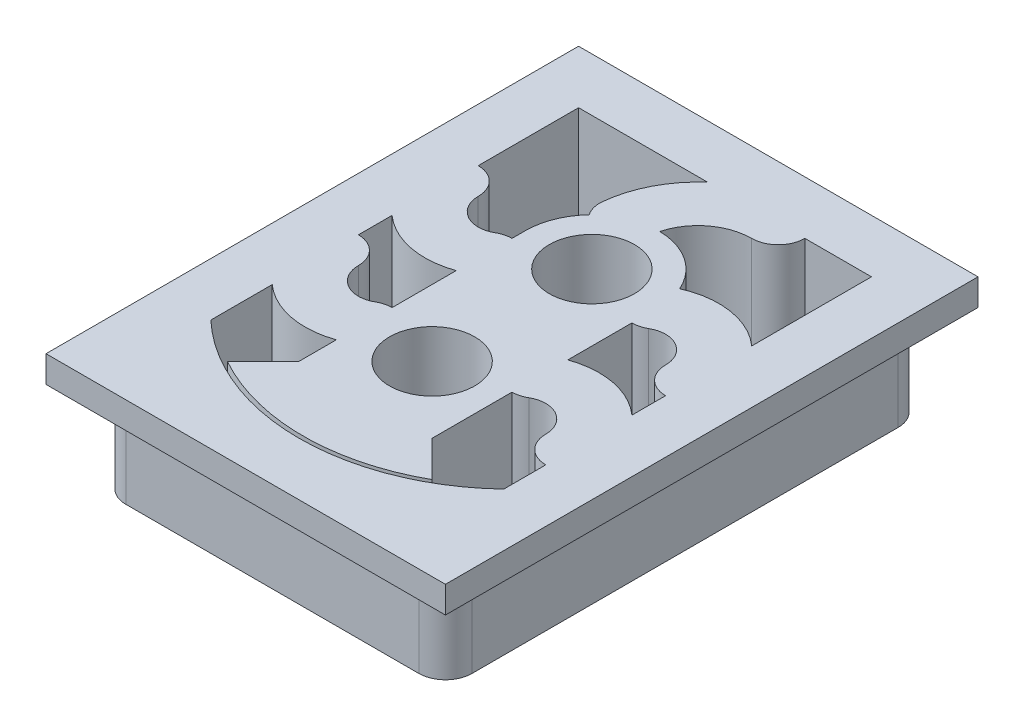
SolidWorks part; units mm, degrees
ref_plane "Front Plane" through (0, 0, 0) normal (0, 0, 1) x (1, 0, 0)
ref_plane "Top Plane" through (0, 0, 0) normal (0, 1, 0) x (1, 0, 0)
ref_plane "Right Plane" through (0, 0, 0) normal (1, 0, 0) x (0, 0, -1)
sketch "Sketch1" plane through (0, 0, 0) normal (0, 1, 0) x (1, 0, 0)
  line L1 (-6.5, -9) -> (6.5, -9)
  line L2 (-6.5, -9) -> (-6.5, 9)
  line L3 (-6.5, 9) -> (6.5, 9)
  line L4 (6.5, -9) -> (6.5, 9)
  line L5 (-6.5, -9) -> (6.5, 9) construction
  line L6 (-6.5, 9) -> (6.5, -9) construction
  point P0 (0, 0)
  dimension "D1" = 18
  dimension "D2" = 13
extrude "Boss-Extrude1" add sketch "Sketch1" along normal blind 3.4
sketch "Sketch2" plane through (0, 3.4, 0) normal (0, 1, 0) x (1, 0, 0)
  line L8 (7.5, -10) -> (7.5, 10)
  line L9 (7.5, 10) -> (-7.5, 10)
  line L10 (-7.5, 10) -> (-7.5, -10)
  line L11 (-7.5, -10) -> (7.5, -10)
  line L12 (7.5, -10) -> (7.5, 10)
  line L13 (7.5, 10) -> (-7.5, 10)
  line L14 (-7.5, 10) -> (-7.5, -10)
  line L15 (-7.5, -10) -> (7.5, -10)
  dimension "D1" = 1
extrude "Boss-Extrude2" add sketch "Sketch2" along normal blind 1
sketch "Sketch4" plane through (0, 0, 0) normal (0, -1, 0) x (1, 0, 0)
  line L0 (-3.8443, 6.8443) -> (-2.5, 5.5)
  line L1 (3.8443, 6.8443) -> (2.5, 5.5)
  line L4 (0, -3) -> (0, 3)
  line L6 (2.5, -5.5) -> (-2.5, -5.5)
  line L7 (2.5, -5.5) -> (2.5, 5.5)
  line L8 (5.5, -8) -> (5.5, 8)
  line L9 (5.5, 8) -> (-5.5, 8)
  line L10 (-5.5, 8) -> (-5.5, -8)
  line L11 (-5.5, -8) -> (5.5, -8)
  line L12 (5.5, -8) -> (5.5, 8)
  line L13 (5.5, 8) -> (-5.5, 8)
  line L14 (-5.5, 8) -> (-5.5, -8)
  line L15 (-5.5, -8) -> (5.5, -8)
  line L16 (2.5, 5.5) -> (-2.5, 5.5)
  line L17 (-2.5, -5.5) -> (-2.5, 5.5)
  line L18 (2.5, -5.5) -> (-2.5, 5.5) construction
  line L19 (2.5, 5.5) -> (-2.5, -5.5) construction
  circle A0 centre (0, 3) radius 1.6
  circle A1 centre (0, -3) radius 1.6
  circle A3 centre (0, -3) radius 2.5
  arc A4 (-2.5, 3) -> (-5.5, 1.2679) centre (-3.5, 1.2679) ccw
  arc A5 (2.5, 1.5) -> (5.5, 3.2321) centre (3.5, 3.2321) ccw
  arc A6 (2.5, -3) -> (5.5, -1.2679) centre (3.5, -1.2679) ccw
  arc A7 (-2.5, -1.5) -> (-5.5, -3.2321) centre (-3.5, -3.2321) ccw
  arc A9 (-1, -5.2913) -> (2, -8) centre (2, -4.9843) ccw
  arc A11 (3.8443, 6.8443) -> (-3.8443, 6.8443) centre (0, 0) ccw
  arc A12 (0, 8) -> (-5.5, 5.8095) centre (0, 0) ccw
  arc A13 (0, 8) -> (5.5, 5.8095) centre (0, 0) cw
  arc A14 (-2, -0.634) -> (-6.5, -3.2321) centre (-3.5, -3.2321) ccw
  arc A15 (-2, 3.866) -> (-6.5, 1.2679) centre (-3.5, 1.2679) ccw
  arc A16 (2, 0.634) -> (6.5, 3.2321) centre (3.5, 3.2321) ccw
  arc A17 (2, -3.866) -> (6.5, -1.2679) centre (3.5, -1.2679) ccw
  arc A18 (-3, -2.366) -> (-4.5, -3.2321) centre (-3.5, -3.2321) ccw
  arc A19 (-3, 2.134) -> (-4.5, 1.2679) centre (-3.5, 1.2679) ccw
  arc A20 (3, 2.366) -> (4.5, 3.2321) centre (3.5, 3.2321) ccw
  arc A21 (3, -2.134) -> (4.5, -1.2679) centre (3.5, -1.2679) ccw
  arc A22 (-2, -0.634) -> (-3, -2.366) centre (-2.5, -1.5) cw
  arc A23 (-6.5, -3.2321) -> (-4.5, -3.2321) centre (-5.5, -3.2321) ccw
  arc A24 (-2, 3.866) -> (-3, 2.134) centre (-2.5, 3) cw
  arc A25 (-6.5, 1.2679) -> (-4.5, 1.2679) centre (-5.5, 1.2679) ccw
  arc A26 (2, 0.634) -> (3, 2.366) centre (2.5, 1.5) cw
  arc A27 (6.5, 3.2321) -> (4.5, 3.2321) centre (5.5, 3.2321) ccw
  arc A28 (2, -3.866) -> (3, -2.134) centre (2.5, -3) cw
  arc A29 (6.5, -1.2679) -> (4.5, -1.2679) centre (5.5, -1.2679) ccw
  arc A31 (-1.9948, -5.3931) -> (2, -9) centre (2, -4.9843) ccw
  arc A33 (-0.0052, -5.1895) -> (2, -7) centre (2, -4.9843) ccw
  arc A36 (-1.9948, -5.3931) -> (-0.0052, -5.1895) centre (-1, -5.2913) cw
  arc A37 (2, -9) -> (2, -7) centre (2, -8) ccw
  point P3 (0, 0)
  point P5 (0, 0)
  dimension "D3" = 3.2
  dimension "D6" = 7.85
  dimension "D8" = 4.5
  dimension "D7" = 2
  dimension "D13" = 135
  dimension "D14" = 1
  dimension "D2" = 6
  dimension "D4" = 11
  dimension "D5" = 5
  dimension "D9" = 4.5
  dimension "D10" = 4.5
  dimension "D11" = 3.5
  dimension "D1" = 1
  dimension "D15" = 1
  dimension "D16" = 1
  dimension "D17" = 1
extrude "Cut-Extrude2" cut sketch "Sketch4" against normal through all
fillet "Fillet1" radius 1 4 edges at (-6.5, 1.7, -9) (6.5, 1.7, -9) (6.5, 1.7, 9) (-6.5, 1.7, 9)
mirror "Mirror2" [suppressed]
delete or keep bodies "Body-Delete/Keep 2" [suppressed] type keep bodies bodies 111
mirror "Mirror1" [suppressed]
delete or keep bodies "Body-Delete/Keep 1" [suppressed] type keep bodies bodies 104
